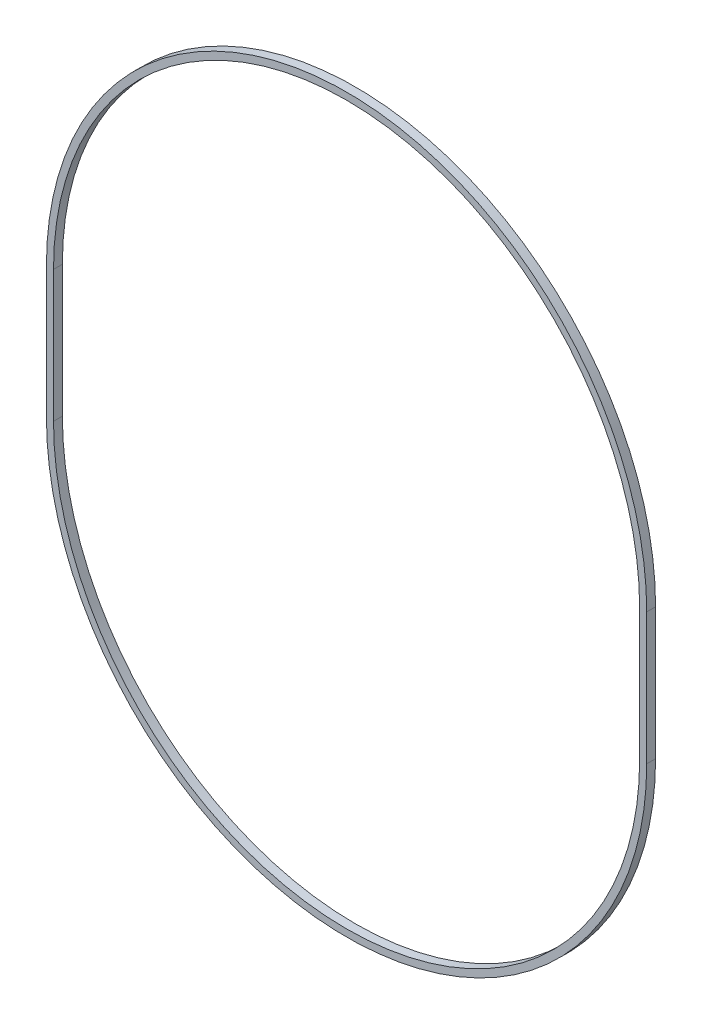
SolidWorks part; units mm, degrees
material "AISI 304"
ref_plane "Front Plane" through (0, 0, 0) normal (0, 0, 1) x (1, 0, 0)
ref_plane "Top Plane" through (0, 0, 0) normal (0, 1, 0) x (1, 0, 0)
ref_plane "Right Plane" through (0, 0, 0) normal (1, 0, 0) x (0, 0, -1)
sketch "Sketch2" plane through (0, 0, 0) normal (0, 0, 1) x (1, 0, 0)
  line B0 (-127.19, 27.875) -> (-127.19, -27.875)
  line B1 (127.19, -27.875) -> (127.19, 27.875)
  line B2 (-98, 27.875) -> (-98, -27.875)
  line B3 (98, -27.875) -> (98, 27.875)
  line B4 (95, -27.875) -> (95, 27.875)
  line B5 (-95, 27.875) -> (-95, -27.875)
  line B6 (124.19, -27.875) -> (124.19, 27.875)
  line B7 (-124.19, 27.875) -> (-124.19, -27.875)
  line B8 (-95, 27.875) -> (-95, -27.875)
  line B9 (95, -27.875) -> (95, 27.875)
  arc B10 (127.19, 27.875) -> (-127.19, 27.875) centre (0, 27.875) ccw
  arc B11 (-127.19, -27.875) -> (127.19, -27.875) centre (0, -27.875) ccw
  arc B12 (98, 27.875) -> (-98, 27.875) centre (0, 27.875) ccw
  arc B13 (-98, -27.875) -> (98, -27.875) centre (0, -27.875) ccw
  arc B14 (95, 27.875) -> (-95, 27.875) centre (0, 27.875) ccw
  arc B15 (-95, -27.875) -> (95, -27.875) centre (0, -27.875) ccw
  arc B16 (-124.19, -27.875) -> (124.19, -27.875) centre (0, -27.875) ccw
  arc B17 (-95, -27.875) -> (95, -27.875) centre (0, -27.875) ccw
  arc B18 (124.19, 27.875) -> (-124.19, 27.875) centre (0, 27.875) ccw
  arc B19 (98, 27.875) -> (-98, 27.875) centre (0, 27.875) ccw
  arc B20 (95, 27.875) -> (-95, 27.875) centre (0, 27.875) ccw
sketch_block_instance "GasketRim-3"
sketch_block "GasketRim"
extrude "Boss-Extrude1" add sketch "Sketch2" along normal mid plane 3.75 contours B0 B11 B1 B10 B18 B6 B16 B7
